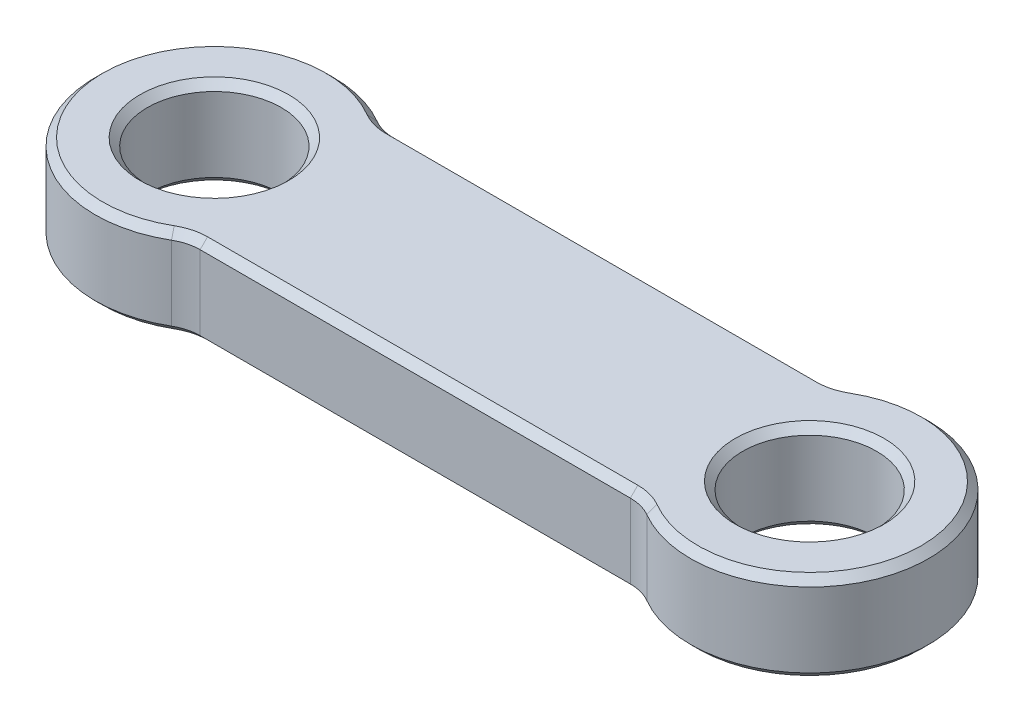
SolidWorks part; units mm, degrees
material "6061 合金"
ref_plane "Front Plane" through (0, 0, 0) normal (0, 0, 1) x (1, 0, 0)
ref_plane "Top Plane" through (0, 0, 0) normal (0, 1, 0) x (1, 0, 0)
ref_plane "Right Plane" through (0, 0, 0) normal (1, 0, 0) x (0, 0, -1)
other "Configuration Table"
sketch "草图1" plane through (0, 0, 0) normal (0, 1, 0) x (1, 0, 0)
  line L0 (-15.3363, 6.5) -> (15.3363, 6.5)
  line L1 (-20, 6.5) -> (20, 6.5) construction
  line L2 (-20, 6.5) -> (-20, -6.5) construction
  line L3 (-20, -6.5) -> (20, -6.5) construction
  line L4 (20, 6.5) -> (20, -6.5) construction
  line L5 (-20, 6.5) -> (20, -6.5) construction
  line L6 (-20, -6.5) -> (20, 6.5) construction
  line L7 (15.3363, -6.5) -> (-15.3363, -6.5)
  arc A0 (-15.3363, -6.5) -> (-15.3363, 6.5) centre (-20, 0) cw
  arc A1 (15.3363, -6.5) -> (15.3363, 6.5) centre (20, 0) ccw
  circle A2 centre (-20, 0) radius 4.5
  circle A3 centre (20, 0) radius 4.5
  point P0 (0, 0)
  dimension "D2" = 8
  dimension "D3" = 8
  dimension "D5" = 9
  dimension "D6" = 9
  dimension "D1" = 40
  dimension "D4" = 13
extrude "凸台-拉伸1" add sketch "草图1" along normal blind 6
fillet "圆角1" radius 3 4 edges at (-15.3363, 3, -6.5) (15.3363, 3, -6.5) (15.3363, 3, 6.5) (-15.3363, 3, 6.5)
chamfer "倒角1" distance 0.5 angle 45 20 edges at (0, 0, 6.5) (15.2381, 0, 6.6041) (-15.2381, 0, 6.6041) (28, 0, 0) (-28, 0, 0) (15.2381, 0, -6.6041) (-15.2381, 0, -6.6041) (0, 0, -6.5) (0, 6, 6.5) (15.2381, 6, 6.6041) (-15.2381, 6, 6.6041) (28, 6, 0) (-28, 6, 0) (15.2381, 6, -6.6041) (-15.2381, 6, -6.6041) (0, 6, -6.5) (20, 0, 4.5) (20, 6, 4.5) (-20, 0, 4.5) (-20, 6, 4.5)
